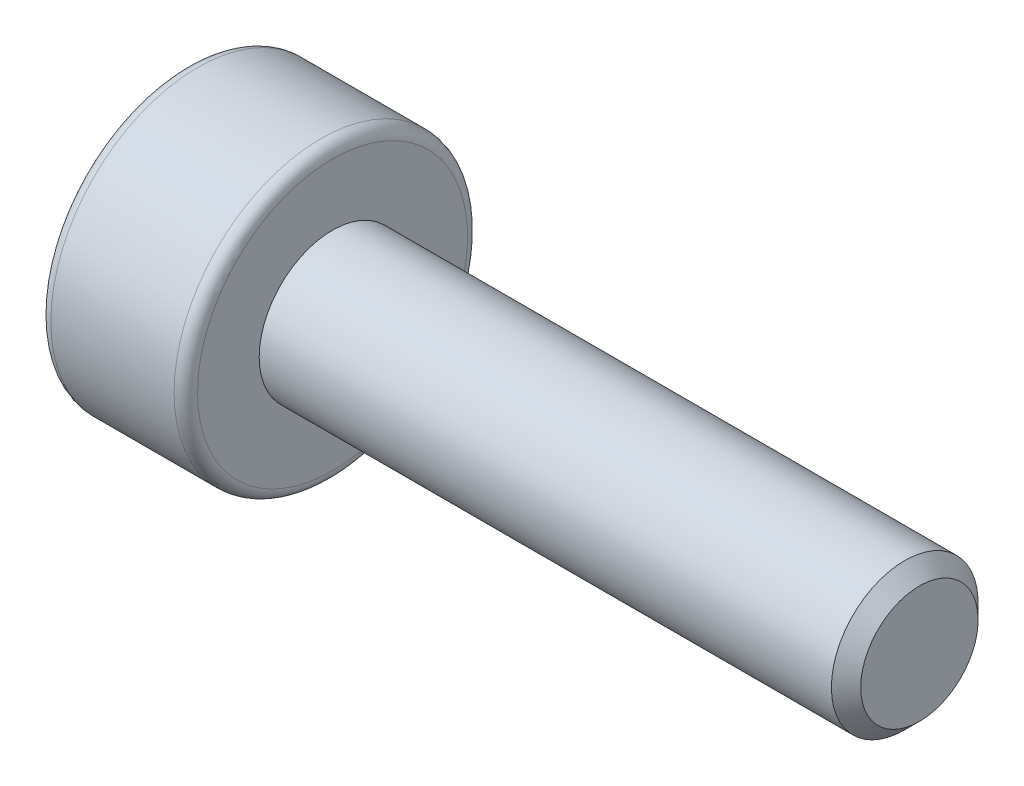
SolidWorks part; units mm, degrees
ref_plane "Front Plane" through (0, 0, 0) normal (0, 0, 1) x (1, 0, 0)
ref_plane "Top Plane" through (0, 0, 0) normal (0, 1, 0) x (1, 0, 0)
ref_plane "Right Plane" through (0, 0, 0) normal (1, 0, 0) x (0, 0, -1)
sketch "Sketch2" plane through (0, 0, 0) normal (0, 0, 1) x (1, 0, 0)
  line L0 (0, 0) -> (0, 2.3)
  line L1 (2.5, 1.25) -> (2.5, 2.3)
  line L2 (2.3, 2.5) -> (0.2, 2.5)
  line L3 (2.5, 1.25) -> (12.25, 1.25)
  line L4 (12.25, 1.25) -> (12.5, 1)
  line L5 (12.5, 1) -> (12.5, 0)
  line L6 (12.5, 0) -> (0, 0)
  line L7 (-2.2818, 0) -> (8.0811, 0) construction
  arc A0 (2.5, 2.3) -> (2.3, 2.5) centre (2.3, 2.3) ccw
  arc A1 (0, 2.3) -> (0.2, 2.5) centre (0.2, 2.3) cw
  point P13 (2.5, 2.5)
  point P16 (0, 2.5)
  dimension "D7" = 0.2
  dimension "D1" = 5
  dimension "D2" = 2.5
  dimension "D3" = 10
  dimension "D4" = 135
  dimension "D5" = 0.25
  dimension "D6" = 2.5
revolve "Revolve1" add sketch "Sketch2" angle 360 about L7
sketch "Sketch3" plane through (0, 0, 0) normal (-1, 0, 0) x (0, 0, 1)
  line L1 (0.5774, -1) -> (1.1547, 0)
  line L2 (1.1547, 0) -> (0.5774, 1)
  line L3 (0.5774, 1) -> (-0.5774, 1)
  line L4 (-0.5774, 1) -> (-1.1547, 0)
  line L5 (-1.1547, 0) -> (-0.5774, -1)
  line L6 (-0.5774, -1) -> (0.5774, -1)
  circle A0 centre (0, 0) radius 1 construction
  dimension "D1" = 2
extrude "Cut-Extrude1" cut sketch "Sketch3" against normal blind 0.8
